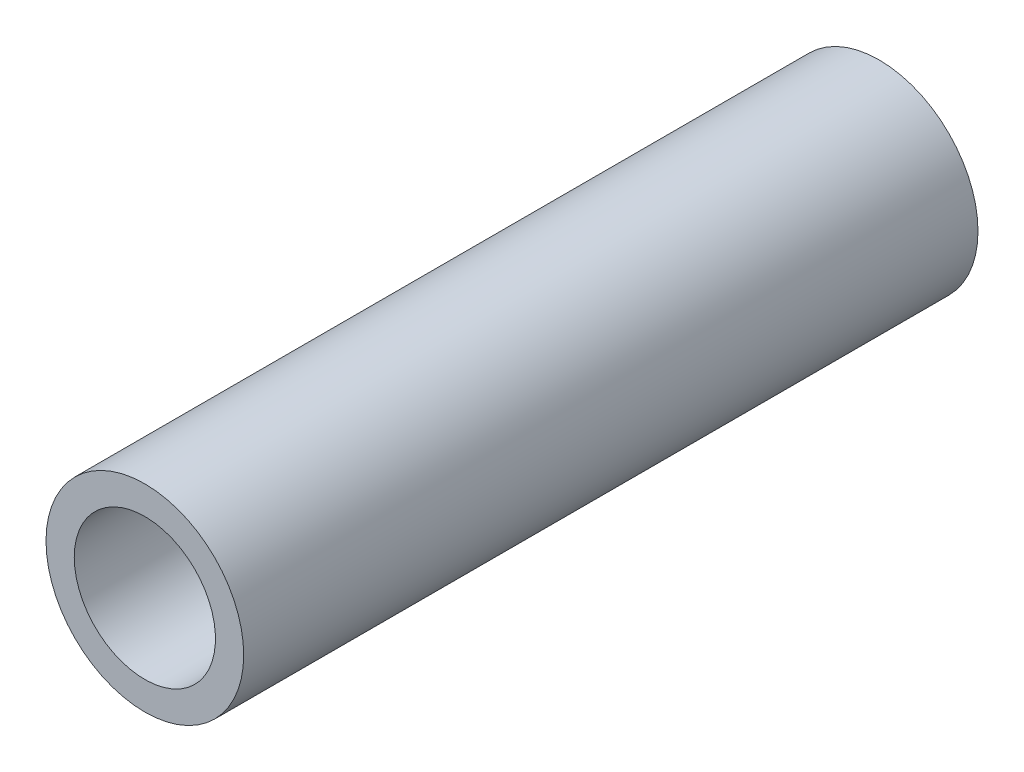
SolidWorks part; units mm, degrees
material "ABS"
ref_plane "前视基准面" through (0, 0, 0) normal (0, 0, 1) x (1, 0, 0)
ref_plane "上视基准面" through (0, 0, 0) normal (0, 1, 0) x (1, 0, 0)
ref_plane "右视基准面" through (0, 0, 0) normal (1, 0, 0) x (0, 0, -1)
sketch "草图1" plane through (0, 0, 0) normal (0, 0, 1) x (1, 0, 0)
  circle A0 centre (0, 0) radius 5
  circle A1 centre (0, 0) radius 7
  dimension "D1" = 10
  dimension "D2" = 14
extrude "凸台-拉伸1" add sketch "草图1" along normal mid plane 52
